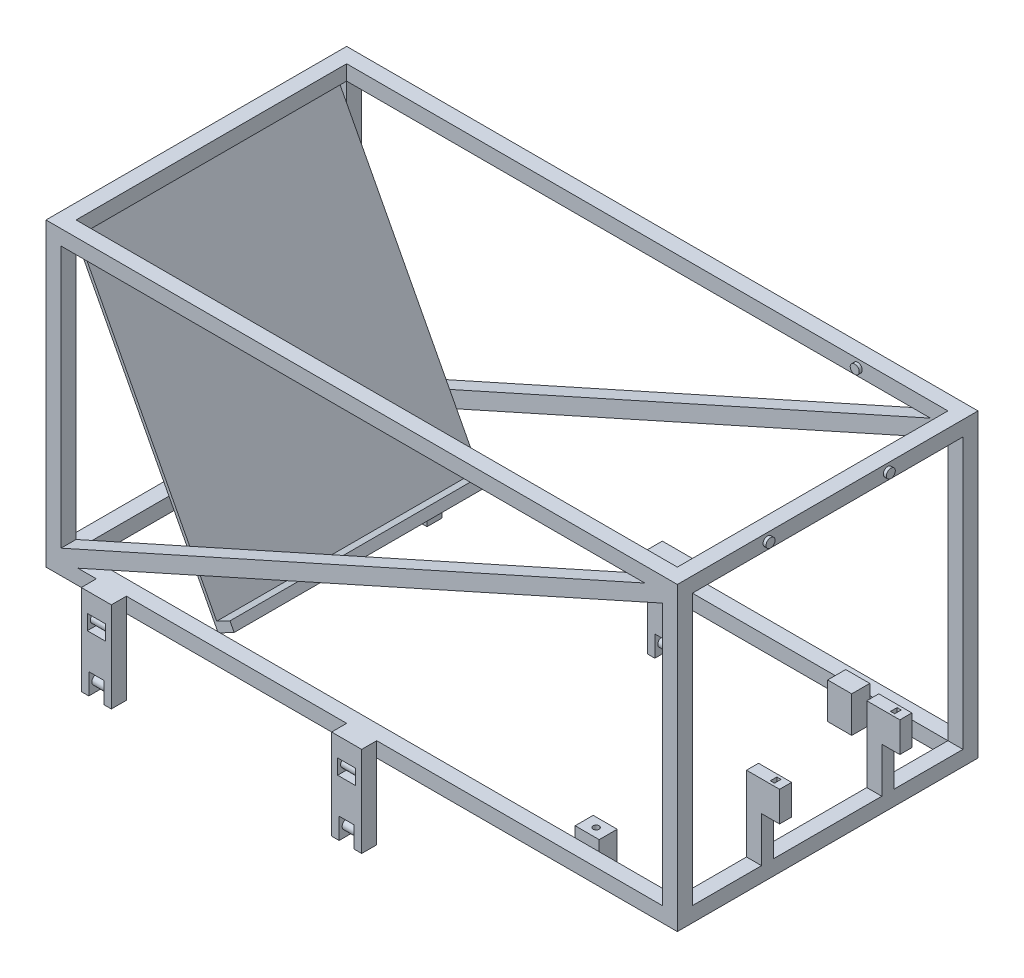
SolidWorks part; units mm, degrees
ref_plane "Front Plane" through (0, 0, 0) normal (0, 0, 1) x (1, 0, 0)
ref_plane "Top Plane" through (0, 0, 0) normal (0, 1, 0) x (1, 0, 0)
ref_plane "Right Plane" through (0, 0, 0) normal (1, 0, 0) x (0, 0, -1)
sketch "Sketch1" plane through (0, 0, 0) normal (0, 1, 0) x (1, 0, 0)
  line L1 (-1050, 500) -> (1050, 500)
  line L2 (-1050, 500) -> (-1050, -500)
  line L3 (-1050, -500) -> (1050, -500)
  line L4 (1050, 500) -> (1050, -500)
  line L5 (-1050, 500) -> (1050, -500) construction
  line L6 (-1050, -500) -> (1050, 500) construction
  point P0 (0, 0)
  dimension "D1" = 2100
  dimension "D2" = 1000
extrude "Boss-Extrude1" add sketch "Sketch1" along normal blind 1000
sketch "Sketch2" plane through (0, 1000, 0) normal (0, 1, 0) x (1, 0, 0)
  line L1 (-1000, 450) -> (1000, 450)
  line L2 (-1000, 450) -> (-1000, -450)
  line L3 (-1000, -450) -> (1000, -450)
  line L4 (1000, 450) -> (1000, -450)
  line L5 (-1000, 450) -> (1000, -450) construction
  line L6 (-1000, -450) -> (1000, 450) construction
  point P0 (0, 0)
  dimension "D1" = 2000
  dimension "D2" = 900
extrude "Cut-Extrude1" cut sketch "Sketch2" against normal through all both and the other way through all
sketch "Sketch3" plane through (0, 0, 500) normal (0, 0, 1) x (1, 0, 0)
  line L0 (0, 0) -> (0, 1182.0357) construction
  line L1 (-1000, 950) -> (1000, 950)
  line L2 (-1000, 950) -> (-1000, 50)
  line L3 (-1000, 50) -> (1000, 50)
  line L4 (1000, 950) -> (1000, 50)
  line L5 (-1000, 950) -> (1000, 50) construction
  line L6 (-1000, 50) -> (1000, 950) construction
  point P0 (0, 500)
  dimension "D1" = 2000
  dimension "D2" = 900
  dimension "D3" = 500
extrude "Cut-Extrude2" cut sketch "Sketch3" against normal through all both and the other way through all
sketch "Sketch4" plane through (-1050, 0, 0) normal (-1, 0, 0) x (0, 0, 1)
  line L0 (0, 0) -> (0, 627.2343) construction
  line L1 (-450, 950) -> (450, 950)
  line L2 (-450, 950) -> (-450, 50)
  line L3 (-450, 50) -> (450, 50)
  line L4 (450, 950) -> (450, 50)
  line L5 (-450, 950) -> (450, 50) construction
  line L6 (-450, 50) -> (450, 950) construction
  point P0 (0, 500)
  dimension "D1" = 900
  dimension "D2" = 900
  dimension "D3" = 500
extrude "Cut-Extrude3" cut sketch "Sketch4" against normal through all both and the other way through all
sketch "Sketch7" plane through (1050, 0, 0) normal (1, 0, 0) x (0, 0, -1)
  line L0 (0, 0) -> (0, 50) construction
  line L1 (450, 50) -> (-450, 50) construction
  circle A0 centre (0, 25) radius 25
  dimension "D1" = 50
sketch "Sketch11" plane through (0, 0, 450) normal (0, 0, -1) x (-1, 0, 0)
  line L0 (-1000, 1000) -> (-700, 1000) construction
  line L1 (-1050, 1000) -> (1050, 1000) construction
  line L2 (-700, 1000) -> (-700, 950) construction
  line L3 (-1000, 950) -> (1000, 950) construction
  circle A0 centre (-700, 975) radius 15
  dimension "D2" = 30
  dimension "D1" = 300
extrude "Boss-Extrude4" add sketch "Sketch11" along normal blind 10
sketch "Sketch13" plane through (0, 0, 450) normal (0, 0, -1) x (-1, 0, 0)
  line L0 (-1000, 50) -> (-700, 50) construction
  line L1 (1000, 50) -> (-1000, 50) construction
  line L2 (-700, 50) -> (-700, 0) construction
  line L3 (-1050, 0) -> (1050, 0) construction
  line L5 (-740, 85) -> (-660, 85)
  line L6 (-740, 85) -> (-740, -35)
  line L7 (-740, -35) -> (-660, -35)
  line L8 (-660, 85) -> (-660, -35)
  line L9 (-740, 85) -> (-660, -35) construction
  line L10 (-740, -35) -> (-660, 85) construction
  point P8 (-700, 25)
  dimension "D1" = 300
  dimension "D2" = 80
  dimension "D3" = 120
extrude "Boss-Extrude6" add sketch "Sketch13" along normal blind 60
sketch "Sketch14" plane through (0, 85, 0) normal (0, 1, 0) x (1, 0, 0)
  line L0 (700, -390) -> (700, -450) construction
  line L1 (660, -390) -> (740, -390) construction
  line L2 (-1000, -450) -> (1000, -450) construction
  line L3 (660, -450) -> (740, -450) construction
  circle A0 centre (700, -420) radius 10
  dimension "D1" = 20
  dimension "D2" = 30
extrude "Cut-Extrude5" cut sketch "Sketch14" against normal through all both and the other way through all
mirror "Mirror3" about plane through (0, 0, 0) normal (0, 0, 1) of "Boss-Extrude4"
sketch "Sketch17" plane through (0, 0, -500) normal (0, 0, -1) x (-1, 0, 0)
  line L0 (-1000, 950) -> (1000, 50) construction
  line L1 (-1000, 921.3298) -> (943.8124, 50)
  line L2 (-1000, 50) -> (-1000, 950) construction
  line L3 (1000, 50) -> (-1000, 50) construction
  line L4 (-941.7224, 950) -> (1000, 79.6071)
  line L5 (-1000, 950) -> (1000, 950) construction
  line L6 (1000, 950) -> (1000, 50) construction
  line L7 (-1000, 921.3298) -> (-1000, 950)
  line L8 (-1000, 950) -> (-941.7224, 950)
  line L9 (943.8124, 50) -> (1000, 50)
  line L10 (1000, 50) -> (1000, 79.6071)
  dimension "D1" = 50
extrude "Boss-Extrude9" add sketch "Sketch17" against normal blind 50
mirror "Mirror4" about plane through (0, 0, 0) normal (0, 0, 1) of "Boss-Extrude9"
sketch "Sketch18" plane through (0, 0, -500) normal (0, 0, -1) x (-1, 0, 0)
  line L0 (-1000, 50) -> (943.8124, 50) construction
  line L1 (0, 0) -> (0, 133.7587) construction
  line L2 (-1050, 0) -> (1050, 0) construction
  line L3 (-882.6259, -180) -> (-857.6259, -180)
  line L4 (-882.6259, 50) -> (-782.6259, 50)
  line L5 (-882.6259, 50) -> (-882.6259, -250)
  line L6 (-882.6259, -250) -> (-857.6259, -250)
  line L7 (-782.6259, 50) -> (-782.6259, -250)
  line L8 (-857.6259, -180) -> (-857.6259, -250)
  line L10 (-807.6259, -250) -> (-807.6259, -180)
  line L11 (-807.6259, -180) -> (-782.6259, -180)
  line L12 (-857.6259, -180) -> (-807.6259, -180)
  line L13 (-807.6259, -250) -> (-782.6259, -250)
  line M13 (943.8124, 50) -> (-1000, 50)
  line M14 (-1050, 0) -> (1050, 0)
  dimension "D1" = 100
  dimension "D2" = 300
  dimension "D3" = 50
  dimension "D4" = 25
  dimension "D5" = 70
  dimension "D6" = 70
extrude "Boss-Extrude10" add sketch "Sketch18" along normal blind 50 contours L8 L3 L5 L6 | L10 L13 L7 L11 | L3 L12 L11 L7 L5 M14 | L7 L5 M13 M14
sketch "Sketch19" plane through (807.6259, 0, 0) normal (1, 0, 0) x (0, 0, -1)
  line L0 (525, -250) -> (525, -180) construction
  line L1 (550, -250) -> (500, -250) construction
  circle A0 centre (525, -215) radius 15
  dimension "D2" = 30
  dimension "D1" = 70
extrude "Boss-Extrude11" add sketch "Sketch19" along normal up to next
mirror "Mirror5" about plane through (0, 0, 0) normal (1, 0, 0) of "Boss-Extrude10", "Boss-Extrude11"
pattern_linear "LPattern1" count 2 spacing 832.6 along (-1, 0, 0) of "Boss-Extrude10", "Boss-Extrude11"
mirror "Mirror6" about plane through (0, 0, 0) normal (0, 0, 1) of "Mirror5", "LPattern1", "Boss-Extrude10", "Boss-Extrude11"
mirror "Mirror7" about plane through (0, 0, 0) normal (0, 0, 1) of "Boss-Extrude6"
sketch "Sketch20" plane through (0, 0, -500) normal (0, 0, -1) x (-1, 0, 0)
  line L0 (1050, 1000) -> (552.1241, 50) construction
  line L1 (782.6259, 50) -> (49.9741, 50) construction
ref_plane "Plane1" through (-412.5965, -216.2335, 0) normal (0.8857, 0.4642, 0) x (0, 0, -1)
sketch "Sketch21" plane through (-412.5965, -216.2335, 0) normal (0.8857, 0.4642, 0) x (0, 0, -1)
  line L0 (450, 1349.928) -> (-450, 1349.928) construction
  line L1 (-434.8755, 1349.928) -> (436.4752, 1349.928)
  line L2 (-434.8755, 1349.928) -> (-434.8755, 279.7646)
  line L3 (-434.8755, 279.7646) -> (436.4752, 279.7646)
  line L4 (436.4752, 1349.928) -> (436.4752, 279.7646)
extrude "Boss-Extrude12" add sketch "Sketch21" along normal blind 10
sketch "Sketch22" plane through (-403.7392, -211.5916, 0) normal (0.8857, 0.4642, 0) x (0, 0, -1)
  line L0 (436.4752, 279.7646) -> (436.4752, 1311.4465) construction
  line L1 (-434.8755, 279.7646) -> (436.4752, 279.7646)
  line L2 (-434.8755, 279.7646) -> (-434.8755, 309.7646)
  line L3 (-434.8755, 309.7646) -> (436.4752, 309.7646)
  line L4 (436.4752, 279.7646) -> (436.4752, 309.7646)
  dimension "D1" = 30
extrude "Boss-Extrude13" add sketch "Sketch22" along normal blind 50
sketch "Sketch23" plane through (0, 50, 0) normal (0, 1, 0) x (1, 0, 0)
  line L1 (782.6259, 550) -> (882.6259, 550)
  line L2 (782.6259, 550) -> (782.6259, 500)
  line L3 (782.6259, 500) -> (882.6259, 500)
  line L4 (882.6259, 550) -> (882.6259, 500)
  line L5 (782.6259, -500) -> (882.6259, -500)
  line L6 (782.6259, -500) -> (782.6259, -550)
  line L7 (782.6259, -550) -> (882.6259, -550)
  line L8 (882.6259, -500) -> (882.6259, -550)
extrude "Cut-Extrude6" cut sketch "Sketch23" against normal through all both and the other way through all
sketch "Sketch24" plane through (1050, 0, 0) normal (1, 0, 0) x (0, 0, -1)
  line L0 (-500, 1000) -> (500, 1000) construction
  line L1 (-200, 1000) -> (-200, 950) construction
  line L2 (-434.8755, 950) -> (436.4752, 950) construction
  circle A0 centre (-200, 975) radius 15
  dimension "D2" = 30
  dimension "D1" = 300
extrude "Boss-Extrude14" add sketch "Sketch24" along normal blind 10
pattern_linear "LPattern2" count 2 spacing 400 along (0, 0, -1) of "Boss-Extrude14"
sketch "Sketch25" plane through (1050, 0, 0) normal (1, 0, 0) x (0, 0, -1)
  line L0 (-500, 0) -> (-200, 0) construction
  line L1 (-500, 0) -> (500, 0) construction
  line L2 (-200, 0) -> (-200, 300) construction
  line L4 (-220, 300) -> (-180, 300)
  line L5 (-220, 300) -> (-220, 0)
  line L6 (-220, 0) -> (-180, 0)
  line L7 (-180, 300) -> (-180, 0)
  line L8 (-220, 300) -> (-180, 0) construction
  line L9 (-220, 0) -> (-180, 300) construction
  point P6 (-200, 150)
  dimension "D1" = 300
  dimension "D2" = 300
  dimension "D3" = 40
extrude "Boss-Extrude15" add sketch "Sketch25" against normal up to surface (50 mm away) up to face at (1000, 485.6649, 475)
sketch "Sketch26" plane through (1050, 0, 0) normal (1, 0, 0) x (0, 0, -1)
  line L0 (-200, 300) -> (-200, 250) construction
  line L1 (-180, 300) -> (-220, 300) construction
  line L3 (-220, 200) -> (-180, 200)
  line L4 (-220, 200) -> (-220, 300)
  line L5 (-220, 300) -> (-180, 300)
  line L6 (-180, 200) -> (-180, 300)
  line L7 (-220, 200) -> (-180, 300) construction
  line L8 (-220, 300) -> (-180, 200) construction
  dimension "D1" = 50
extrude "Boss-Extrude16" add sketch "Sketch26" along normal blind 60
sketch "Sketch27" plane through (0, 300, 0) normal (0, 1, 0) x (1, 0, 0)
  line L0 (1050, -180) -> (1070, -180) construction
  line L1 (1000, -180) -> (1110, -180) construction
  line L2 (1000, -220) -> (1110, -220) construction
  line L3 (1070, -180) -> (1084, -180)
  line L4 (1070, -180) -> (1070, -220)
  line L5 (1070, -220) -> (1084, -220)
  line L6 (1084, -180) -> (1084, -220)
  line L7 (1070, -189) -> (1084, -189)
  line L8 (1070, -211) -> (1084, -211)
  line L9 (1070, -200) -> (1172.1606, -200) construction
  dimension "D1" = 20
  dimension "D2" = 22
  dimension "D3" = 14
extrude "Cut-Extrude7" cut sketch "Sketch27" against normal through all both and the other way through all contours L4 L8 L6 L7
pattern_linear "LPattern3" count 2 spacing 400 along (0, 0, -1) of "Boss-Extrude16", "Boss-Extrude15", "Cut-Extrude7"
sketch "Sketch29" plane through (-882.6259, 0, 0) normal (-1, 0, 0) x (0, 0, 1)
  line L0 (-525, -215) -> (-525, -39.5) construction
  line L1 (-500, 0) -> (-500, -250) construction
  line L2 (-550, -14.5) -> (-500, -14.5)
  line L3 (-550, -14.5) -> (-550, -64.5)
  line L4 (-550, -64.5) -> (-500, -64.5)
  line L5 (-500, -14.5) -> (-500, -64.5)
  line L6 (-550, -14.5) -> (-500, -64.5) construction
  line L7 (-550, -64.5) -> (-500, -14.5) construction
  circle A0 centre (-525, -215) radius 15 construction
  circle A1 centre (-525, -215) radius 15
  line M5 (-550, 50) -> (-550, -250)
  line M7 (-500, -250) -> (-500, 0)
  dimension "D1" = 175.5
  dimension "D2" = 50
extrude "Cut-Extrude8" cut sketch "Sketch29" against normal blind 60 from offset 20 contours L4 L2 M5 M7 offset against normal yes
sketch "Sketch30" plane through (-802.6259, 0, 0) normal (-1, 0, 0) x (0, 0, 1)
  line L0 (-550, -14.5) -> (-500, -14.5) construction
  line L1 (-525, -14.5) -> (-525, -64.5) construction
  circle A0 centre (-525, -39.5) radius 15
  dimension "D2" = 30
  dimension "D1" = 50
extrude "Boss-Extrude17" add sketch "Sketch30" along normal up to next
sketch "Sketch31" plane through (50.0259, 0, 0) normal (1, 0, 0) x (0, 0, -1)
  line L0 (525, -215) -> (525, -39.5) construction
  line L1 (550, 50) -> (550, -250) construction
  line L2 (500, -14.5) -> (550, -14.5)
  line L3 (500, -14.5) -> (500, -64.5)
  line L4 (500, -64.5) -> (550, -64.5)
  line L5 (550, -14.5) -> (550, -64.5)
  line L6 (500, -14.5) -> (550, -64.5) construction
  line L7 (500, -64.5) -> (550, -14.5) construction
  circle A0 centre (525, -215) radius 15 construction
  circle A1 centre (525, -215) radius 15
  line M5 (500, 0) -> (500, -250)
  line M7 (550, -250) -> (550, 50)
  dimension "D1" = 175.5
  dimension "D2" = 50
extrude "Cut-Extrude9" cut sketch "Sketch31" against normal blind 60 from offset 20 contours L4 L2 M5 M7 offset against normal yes
sketch "Sketch32" plane through (-29.9741, 0, 0) normal (1, 0, 0) x (0, 0, -1)
  line L0 (500, -14.5) -> (550, -14.5) construction
  line L1 (525, -14.5) -> (525, -64.5) construction
  circle A0 centre (525, -39.5) radius 15
  dimension "D2" = 30
  dimension "D1" = 50
extrude "Boss-Extrude18" add sketch "Sketch32" along normal up to next
mirror "Mirror8" about plane through (0, 0, 0) normal (0, 0, 1) of "Cut-Extrude9", "Boss-Extrude18", "Boss-Extrude17", "Cut-Extrude8"
